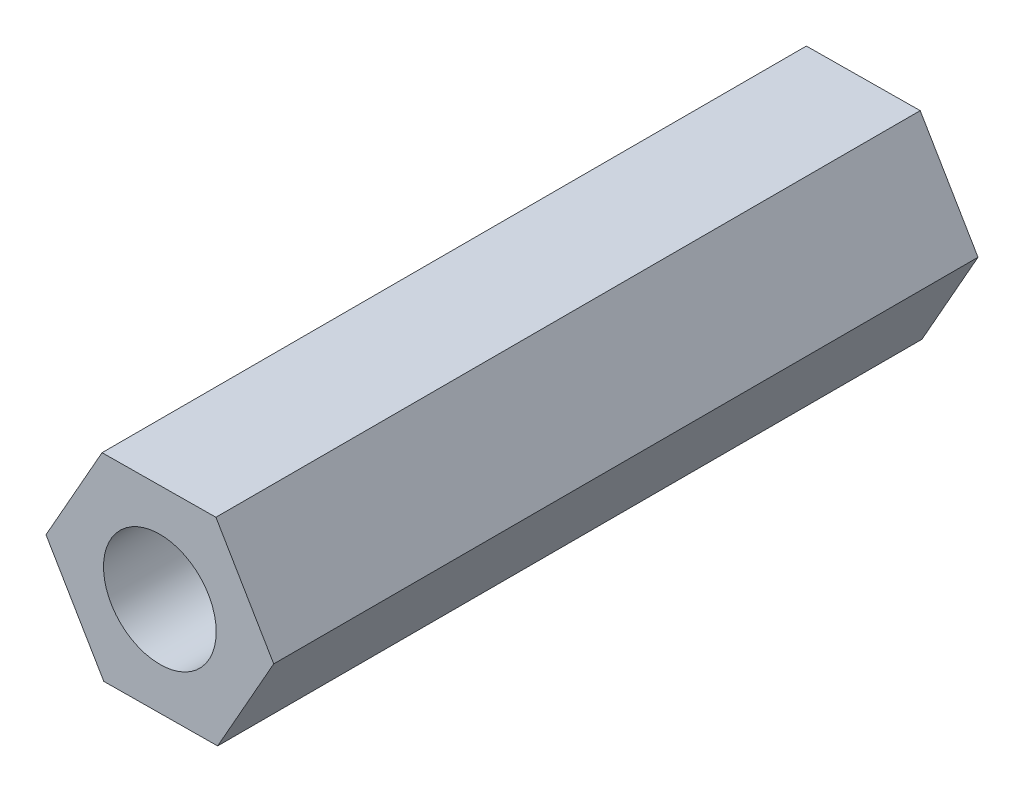
SolidWorks part; units mm, degrees
ref_plane "前视基准面" through (0, 0, 0) normal (0, 0, 1) x (1, 0, 0)
ref_plane "上视基准面" through (0, 0, 0) normal (0, 1, 0) x (1, 0, 0)
ref_plane "右视基准面" through (0, 0, 0) normal (1, 0, 0) x (0, 0, -1)
sketch "草图1" plane through (0, 0, 0) normal (0, 0, 1) x (1, 0, 0)
  line L1 (2.0515, -3.4821) -> (4.0413, 0.0356)
  line L2 (4.0413, 0.0356) -> (1.9898, 3.5177)
  line L3 (1.9898, 3.5177) -> (-2.0515, 3.4821)
  line L4 (-2.0515, 3.4821) -> (-4.0413, -0.0356)
  line L5 (-4.0413, -0.0356) -> (-1.9898, -3.5177)
  line L6 (-1.9898, -3.5177) -> (2.0515, -3.4821)
  circle A0 centre (0, 0) radius 3.5 construction
  circle A1 centre (0, 0) radius 2
extrude "凸台-拉伸1" add sketch "草图1" along normal blind 25
